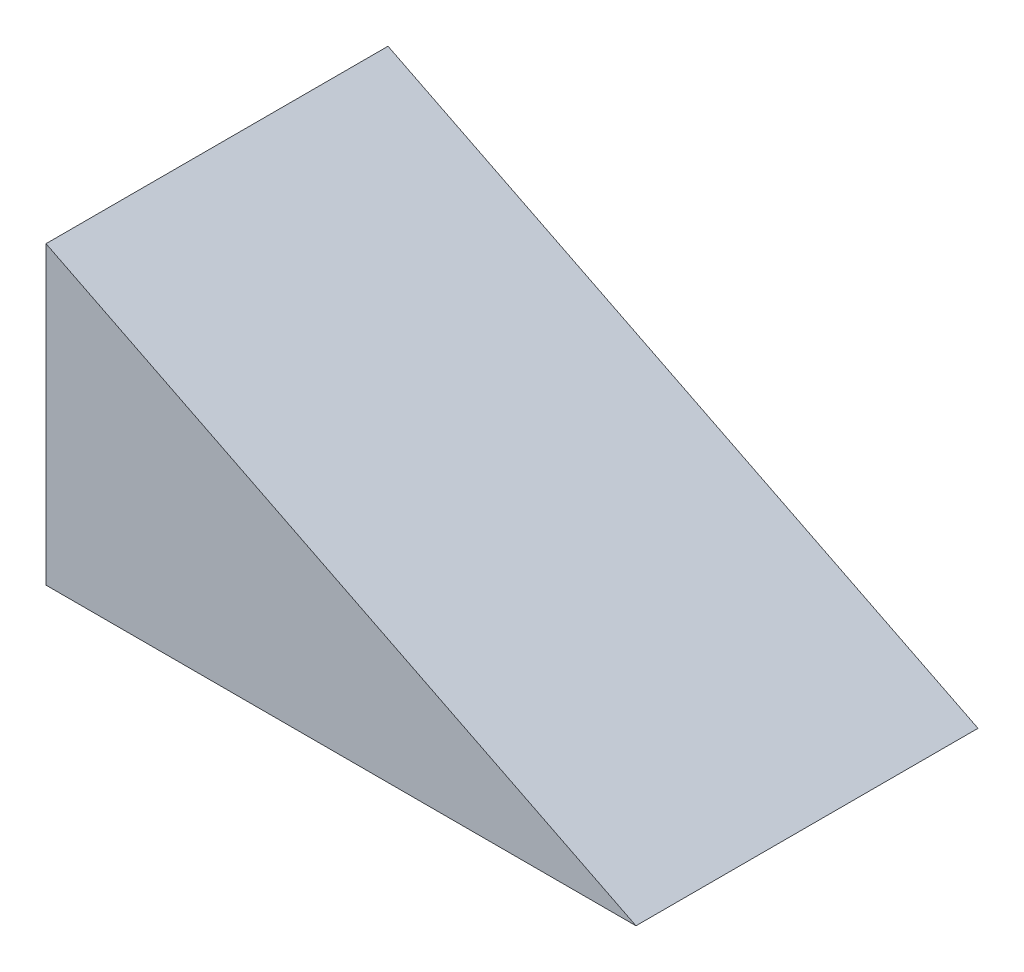
SolidWorks part; units mm, degrees
ref_plane "前视基准面" through (0, 0, 0) normal (0, 0, 1) x (1, 0, 0)
ref_plane "上视基准面" through (0, 0, 0) normal (0, 1, 0) x (1, 0, 0)
ref_plane "右视基准面" through (0, 0, 0) normal (1, 0, 0) x (0, 0, -1)
sketch "草图1" plane through (0, 0, 0) normal (0, 0, 1) x (1, 0, 0)
  line L0 (0, 0) -> (0, 518.795)
  line L1 (0, 518.795) -> (1035, 0)
  line L2 (1035, 0) -> (0, 0)
  dimension "D1" = 1035
  dimension "D2" = 518.795
extrude "凸台-拉伸2" add sketch "草图1" against normal blind 600
